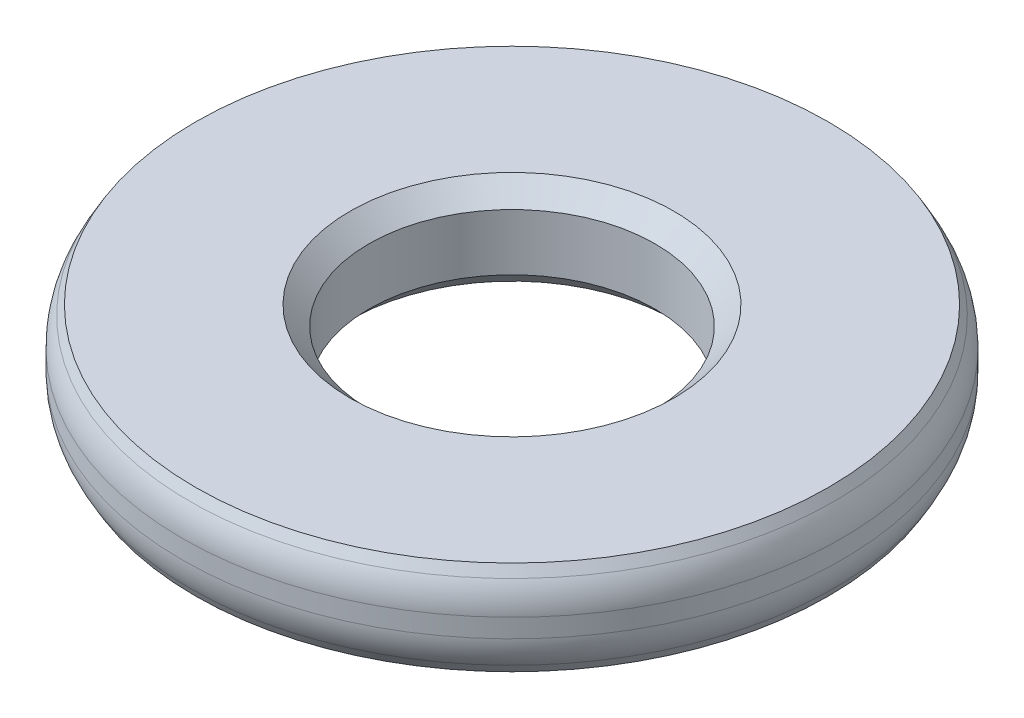
SolidWorks part; units mm, degrees
ref_plane "정면" through (0, 0, 0) normal (0, 0, 1) x (1, 0, 0)
ref_plane "윗면" through (0, 0, 0) normal (0, 1, 0) x (1, 0, 0)
ref_plane "우측면" through (0, 0, 0) normal (1, 0, 0) x (0, 0, -1)
sketch "스케치1" plane through (0, 0, 0) normal (0, 1, 0) x (1, 0, 0)
  circle A0 centre (0, 0) radius 17.5
  dimension "D1" = 35
extrude "보스-돌출1" add sketch "스케치1" along normal blind 5
sketch "스케치2" plane through (0, 5, 0) normal (0, 1, 0) x (1, 0, 0)
  circle A0 centre (0, 0) radius 7.6
  dimension "D1" = 15.2
extrude "컷-돌출1" cut sketch "스케치2" against normal through all both and the other way through all
chamfer "모따기1" distance 1.2 angle 30 2 edges at (0, 0, 17.5) (0, 5, 17.5)
fillet "필렛1" radius 3 2 edges at (0, 1.2, 17.5) (0, 3.8, 17.5)
chamfer "모따기2" distance 1 angle 45 2 edges at (0, 0, 7.6) (0, 5, 7.6)
